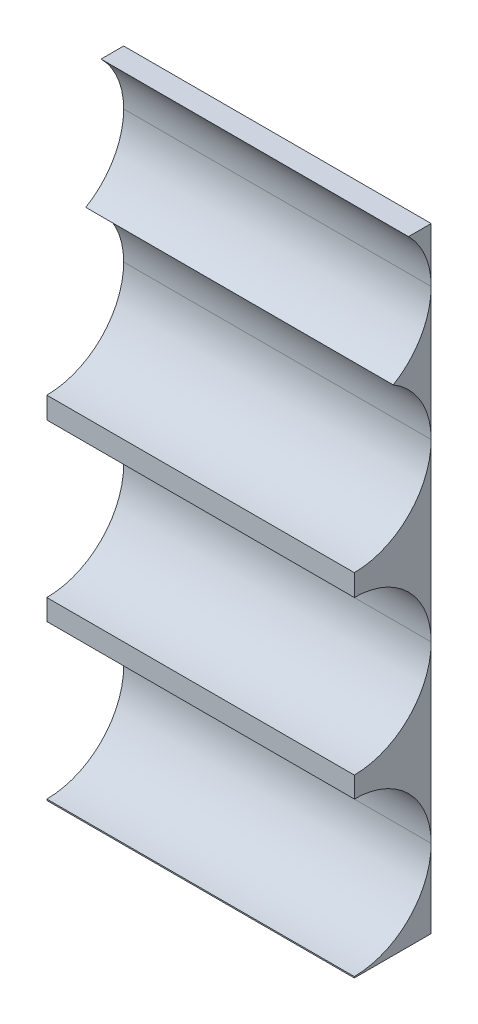
SolidWorks part; units mm, degrees
ref_plane "前视基准面" through (0, 0, 0) normal (0, 0, 1) x (1, 0, 0)
ref_plane "上视基准面" through (0, 0, 0) normal (0, 1, 0) x (1, 0, 0)
ref_plane "右视基准面" through (0, 0, 0) normal (1, 0, 0) x (0, 0, -1)
sketch "草图1" plane through (0, 0, 0) normal (0, 0, 1) x (1, 0, 0)
  line L1 (0, 0) -> (8, 0)
  line L2 (0, 0) -> (0, 16)
  line L3 (0, 16) -> (8, 16)
  line L4 (8, 0) -> (8, 16)
extrude "凸台-拉伸1" add sketch "草图1" along normal blind 2
sketch "草图3" plane through (0, 0, 0) normal (-1, 0, 0) x (0, 0, 1)
  line L0 (2, 16) -> (2, 0) construction
  line L1 (0.5893, 16) -> (2, 16)
  line L2 (2, 16) -> (2, 9.1331)
  line L3 (2, 4.0325) -> (2, 0.0325)
  line L4 (2, 8.573) -> (2, 4.573)
  arc A0 (2, 4.0325) -> (2, 0.0325) centre (2, 2.0325) ccw
  arc A1 (2, 8.573) -> (2, 4.573) centre (2, 6.573) ccw
  arc A2 (0.9872, 12.8577) -> (2, 9.1331) centre (2, 11.1331) ccw
  arc A3 (0.5893, 16) -> (0.9872, 12.8577) centre (2, 14.5823) ccw
extrude "切除-拉伸1" cut sketch "草图3" against normal up to surface (8 mm away) up to face at (8, 8, 1)
